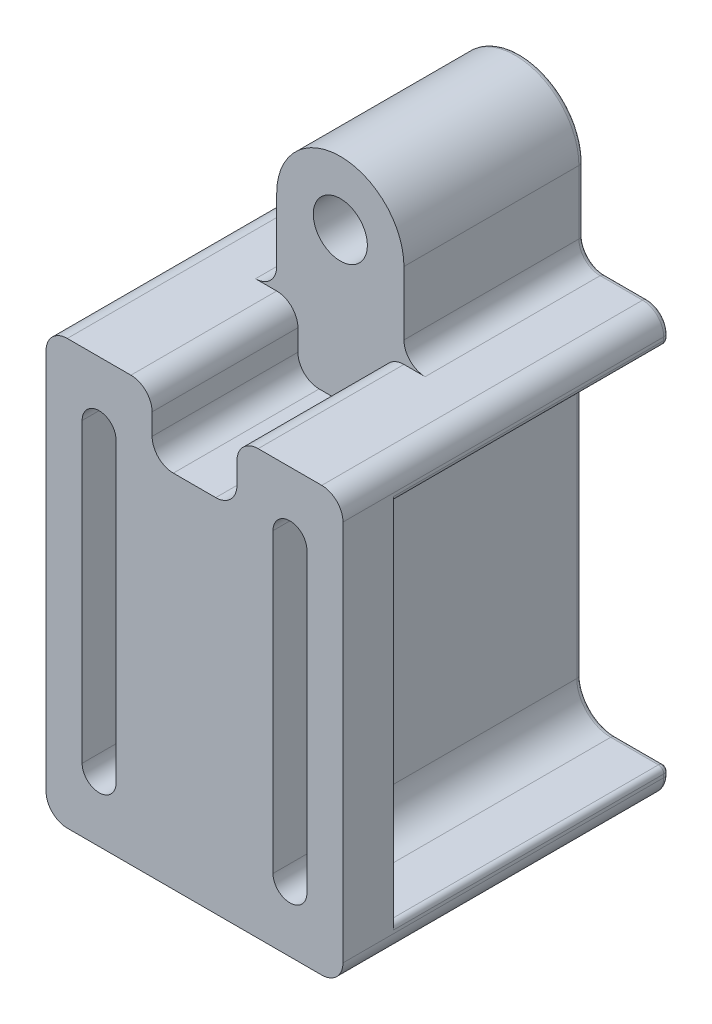
SolidWorks part; units mm, degrees
ref_plane "Front Plane" through (0, 0, 0) normal (0, 0, 1) x (1, 0, 0)
ref_plane "Top Plane" through (0, 0, 0) normal (0, 1, 0) x (1, 0, 0)
ref_plane "Right Plane" through (0, 0, 0) normal (1, 0, 0) x (0, 0, -1)
sketch "Sketch1" plane through (0, 0, 0) normal (0, 0, 1) x (1, 0, 0)
  circle A0 centre (0, 0) radius 1.9
  circle A1 centre (0, 0) radius 6
  dimension "D1" = 3.8
  dimension "D2" = 12
extrude "Boss-Extrude1" add sketch "Sketch1" along normal blind 6
sketch "Sketch2" plane through (0, 0, 6) normal (0, 0, 1) x (1, 0, 0)
  circle A0 centre (0, 0) radius 2.55
  circle A1 centre (0, 0) radius 6 construction
  circle A2 centre (0, 0) radius 6
  dimension "D1" = 5.1
extrude "Boss-Extrude2" add sketch "Sketch2" along normal blind 11
sketch "Sketch3" plane through (0, 0, 0) normal (0, 0, -1) x (-1, 0, 0)
  line L0 (0, 0) -> (0, -16) construction
  line L1 (-6, 0) -> (-6, -16)
  line L2 (-6, -16) -> (6, -16)
  line L3 (6, -16) -> (6, 0)
  circle A0 centre (0, 0) radius 6 construction
  arc A1 (6, 0) -> (-6, 0) centre (0, 0) ccw
  circle A5 centre (0, 0) radius 2.55 construction
  circle A6 centre (0, 0) radius 2.55
  dimension "D1" = 16
extrude "Boss-Extrude3" add sketch "Sketch3" against normal up to surface (17 mm away) up to face at (6, 0, 17)
sketch "Sketch4" plane through (0, 0, 0) normal (0, 0, -1) x (-1, 0, 0)
  line L2 (-6, -16) -> (-6, -8)
  line L3 (-6, -8) -> (-14, -8)
  line L6 (6, -16) -> (6, -8)
  line L7 (6, -8) -> (14, -8)
  line L9 (-14, -48) -> (14, -48)
  line L11 (14, -8) -> (14, -48)
  line L12 (-14, -8) -> (-14, -48)
  line L13 (6, -16) -> (6, 0) construction
  line L14 (-6, 0) -> (-6, -16)
  line L15 (-6, -16) -> (6, -16)
  line L16 (6, -16) -> (6, 0)
  line L18 (-6, -16) -> (6, -16)
  arc A1 (6, 0) -> (-6, 0) centre (0, 0) ccw
  dimension "D1" = 8
  dimension "D2" = 0
  dimension "D3" = 40
  dimension "D4" = 8
extrude "Boss-Extrude4" add sketch "Sketch4" against normal blind 30.75
sketch "Sketch9" plane through (0, 0, 17) normal (0, 0, 1) x (1, 0, 0)
  line L0 (-6, -8) -> (-4, -8)
  line L1 (-4, -8) -> (-4, -14)
  line L2 (-4, -14) -> (4, -14)
  line L3 (4, -14) -> (4, -8)
  line L4 (4, -8) -> (6, -8)
  line L5 (6, -8) -> (6, -16)
  line L6 (6, -16) -> (-6, -16)
  line L7 (-6, -16) -> (-6, -8)
  line L8 (-1.2081, -14) -> (-1.2081, -16) construction
  dimension "D1" = 2
extrude "Boss-Extrude6" add sketch "Sketch9" along normal up to surface (13.75 mm away) up to face at (0, -20, 30.75)
sketch "Sketch5" plane through (0, 0, 0) normal (0, 0, -1) x (-1, 0, 0)
  line L0 (-14, -8) -> (-14, -48) construction
  line L1 (-6, -8) -> (-14, -8) construction
  line L2 (-14, -48) -> (14, -48) construction
  line L3 (0, 0) -> (0, -10.9168) construction
  line L4 (-9, -14) -> (-9, -42) construction
  line L5 (-5.8, -14) -> (-5.8, -42)
  line L6 (-12.2, -14) -> (-12.2, -42)
  line L7 (9, -14) -> (9, -42) construction
  line L8 (5.8, -14) -> (5.8, -42)
  line L9 (12.2, -14) -> (12.2, -42)
  arc A0 (-5.8, -14) -> (-12.2, -14) centre (-9, -14) ccw
  arc A1 (-12.2, -42) -> (-5.8, -42) centre (-9, -42) ccw
  arc A2 (5.8, -14) -> (12.2, -14) centre (9, -14) cw
  arc A3 (12.2, -42) -> (5.8, -42) centre (9, -42) cw
  point P11 (-9, -28)
  point P19 (9, -28)
  dimension "D1" = 3.2
  dimension "D2" = 6
  dimension "D3" = 6
  dimension "D4" = 5
extrude "Cut-Extrude1" cut sketch "Sketch5" against normal blind 26
sketch "Sketch7" plane through (0, 0, 0) normal (0, 0, -1) x (-1, 0, 0)
  line L0 (0, 0) -> (0, -13.9676) construction
  line L1 (-9, -14) -> (-9, -42) construction
  line L2 (-7.4, -14) -> (-7.4, -42)
  line L3 (-10.6, -14) -> (-10.6, -42)
  line L4 (9, -14) -> (9, -42) construction
  line L5 (7.4, -14) -> (7.4, -42)
  line L6 (10.6, -14) -> (10.6, -42)
  arc A0 (-7.4, -14) -> (-10.6, -14) centre (-9, -14) ccw
  arc A1 (-10.6, -42) -> (-7.4, -42) centre (-9, -42) ccw
  arc A2 (7.4, -14) -> (10.6, -14) centre (9, -14) cw
  arc A3 (10.6, -42) -> (7.4, -42) centre (9, -42) cw
  point P7 (-9, -28)
  point P14 (9, -28)
  dimension "D1" = 1.6
extrude "Cut-Extrude2" cut sketch "Sketch7" against normal through all
fillet "Fillet1" radius 2 6 edges at (6, -8, 8.5) (-6, -8, 8.5) (-14, -48, 15.375) (-14, -8, 15.375) (14, -48, 15.375) (14, -8, 15.375)
fillet "Fillet2" radius 2 4 edges at (4, -8, 23.875) (4, -14, 23.875) (-4, -14, 23.875) (-4, -8, 23.875)
sketch "Sketch10" plane through (0, 0, 0) normal (0, 0, -1) x (-1, 0, 0)
  line L1 (0, 3.3486) -> (-2.9, 1.6743)
  line L2 (-2.9, 1.6743) -> (-2.9, -1.6743)
  line L3 (-2.9, -1.6743) -> (0, -3.3486)
  line L4 (0, -3.3486) -> (2.9, -1.6743)
  line L5 (2.9, -1.6743) -> (2.9, 1.6743)
  line L6 (2.9, 1.6743) -> (0, 3.3486)
  circle A0 centre (0, 0) radius 2.9 construction
  dimension "D1" = 5.8
extrude "Cut-Extrude3" cut sketch "Sketch10" against normal blind 3
sketch "Sketch12" plane through (0, 0, 0) normal (0, 0, -1) x (-1, 0, 0)
  line L0 (-9, -10.8) -> (-14, -10.8)
  line L1 (-14, -10) -> (-14, -46) construction
  line L2 (-14, -10.8) -> (-14, -45.2)
  line L3 (-14, -45.2) -> (-9, -45.2)
  line L4 (-9, -45.2) -> (-9, -10.8)
  line L5 (9, -10.8) -> (14, -10.8)
  line L6 (14, -46) -> (14, -10) construction
  line L7 (14, -10.8) -> (14, -45.2)
  line L8 (14, -45.2) -> (9, -45.2)
  line L9 (9, -45.2) -> (9, -10.8)
  arc A0 (-5.8, -14) -> (-12.2, -14) centre (-9, -14) ccw construction
  arc A1 (-12.2, -42) -> (-5.8, -42) centre (-9, -42) ccw construction
  arc A2 (12.2, -14) -> (5.8, -14) centre (9, -14) ccw construction
  arc A3 (5.8, -42) -> (12.2, -42) centre (9, -42) ccw construction
extrude "Cut-Extrude4" cut sketch "Sketch12" against normal up to surface (26 mm away) and the other way through all up to face at (9, -28, 26)
fillet "Fillet3" radius 0.5 36 edges at (10, -8, 0) (-10, -8, 0) (-6, -3, 0) (0, -48, 0) (14, -10.4, 0) (-14, -45.6, 0) (13.4142, -8.5858, 0) (13.4142, -47.4142, 0) (-13.4142, -8.5858, 0) (-13.4142, -47.4142, 0) (6.5858, -7.4142, 0) (-6.5858, -7.4142, 0) (0, 6, 0) (6, -3, 0) (-1.45, 2.5115, 0) (1.45, 2.5115, 0) (2.9, 0, 0) (1.45, -2.5115, 0) (-1.45, -2.5115, 0) (-2.9, 0, 0) (14, -45.6, 0) (-14, -10.4, 0) (14, -45.2, 13) (14, -10.8, 13) (-14, -10.8, 13) (-14, -45.2, 13) (5.8, -28, 0) (-5.8, -28, 0)
sketch "Sketch8" plane through (0, 0, 26) normal (0, 0, -1) x (-1, 0, 0)
  line L0 (10.6, -14) -> (10.6, -42) construction
  line L1 (7.4, -42) -> (7.4, -14) construction
  line L2 (-7.4, -42) -> (-7.4, -14) construction
  line L3 (-10.6, -14) -> (-10.6, -42) construction
  line L4 (10.6, -14) -> (10.6, -42)
  line L5 (7.4, -42) -> (7.4, -14)
  line L6 (-7.4, -42) -> (-7.4, -14)
  line L7 (-10.6, -14) -> (-10.6, -42)
  line L8 (-6.9, -42) -> (-6.9, -14)
  line L9 (-11.1, -14) -> (-11.1, -42)
  line L10 (11.1, -14) -> (11.1, -42)
  line L11 (6.9, -42) -> (6.9, -14)
  arc A0 (10.6, -14) -> (7.4, -14) centre (9, -14) ccw construction
  arc A1 (7.4, -42) -> (10.6, -42) centre (9, -42) ccw construction
  arc A2 (-10.6, -42) -> (-7.4, -42) centre (-9, -42) ccw construction
  arc A3 (-7.4, -14) -> (-10.6, -14) centre (-9, -14) ccw construction
  arc A4 (10.6, -14) -> (7.4, -14) centre (9, -14) ccw
  arc A5 (7.4, -42) -> (10.6, -42) centre (9, -42) ccw
  arc A6 (-10.6, -42) -> (-7.4, -42) centre (-9, -42) ccw
  arc A7 (-7.4, -14) -> (-10.6, -14) centre (-9, -14) ccw
  arc A8 (-11.1, -42) -> (-6.9, -42) centre (-9, -42) ccw
  arc A9 (-6.9, -14) -> (-11.1, -14) centre (-9, -14) ccw
  arc A10 (6.9, -42) -> (11.1, -42) centre (9, -42) ccw
  arc A11 (11.1, -14) -> (6.9, -14) centre (9, -14) ccw
  dimension "D1" = 0.5
extrude "Boss-Extrude5" [suppressed] add sketch "Sketch8" along normal up to surface (6 mm away)
equation "\"D3@Sketch5\"=\"D2@Sketch5\""
